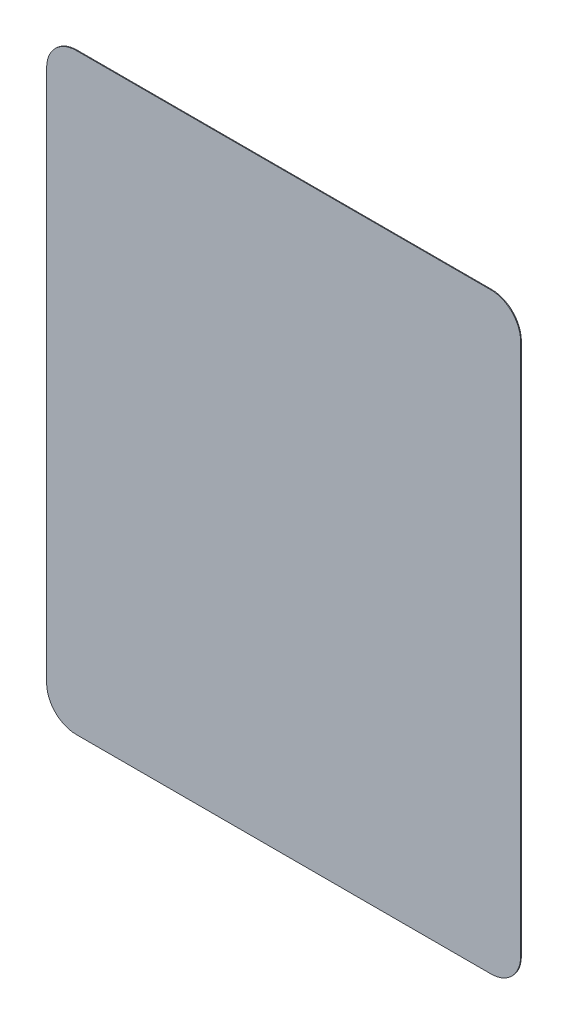
SolidWorks part; units mm, degrees
ref_plane "Front Plane" through (0, 0, 0) normal (0, 0, 1) x (1, 0, 0)
ref_plane "Top Plane" through (0, 0, 0) normal (0, 1, 0) x (1, 0, 0)
ref_plane "Right Plane" through (0, 0, 0) normal (1, 0, 0) x (0, 0, -1)
sketch "Sketch1" plane through (0, 0, 0) normal (0, 0, 1) x (1, 0, 0)
  line L14 (0, 25) -> (0, -25) construction
  line L25 (-5, -25) -> (5, -25)
  line L49 (0, 25) -> (-17.5, 25)
  line L50 (0, 25) -> (17.5, 25)
  line L51 (-5, -25) -> (5, -25) construction
  line L56 (-20, 22.5) -> (-20, -22.5)
  line L57 (-17.5, -25) -> (-5, -25)
  line L58 (20, 22.5) -> (20, -22.5)
  line L59 (17.5, -25) -> (5, -25)
  arc A0 (17.5, 25) -> (20, 22.5) centre (17.5, 22.5) cw
  arc A1 (20, -22.5) -> (17.5, -25) centre (17.5, -22.5) cw
  arc A2 (-17.5, -25) -> (-20, -22.5) centre (-17.5, -22.5) cw
  arc A3 (-20, 22.5) -> (-17.5, 25) centre (-17.5, 22.5) cw
  point P0 (0, 0)
  point P8 (20, 25)
  point P17 (-20, 25)
  dimension "D1" = 2.5
  dimension "D2" = 25
  dimension "D4" = 25
  dimension "D20" = 20
  dimension "D21" = 20
  dimension "D22" = 25
extrude "Boss-Extrude1" add sketch "Sketch1" along normal blind 0.065
